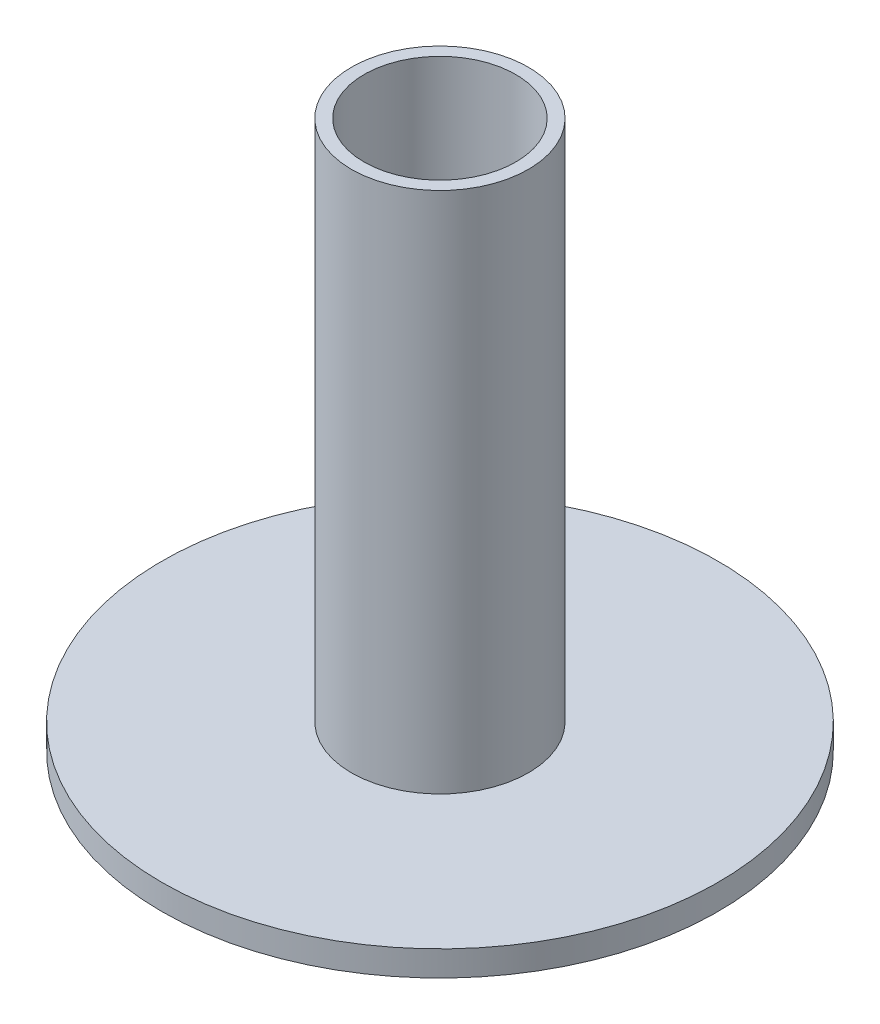
SolidWorks part; units mm, degrees
ref_plane "Alzado" through (0, 0, 0) normal (0, 0, 1) x (1, 0, 0)
ref_plane "Planta" through (0, 0, 0) normal (0, 1, 0) x (1, 0, 0)
ref_plane "Vista lateral" through (0, 0, 0) normal (1, 0, 0) x (0, 0, -1)
sketch "Croquis1" plane through (0, 0, 0) normal (0, 1, 0) x (1, 0, 0)
  circle A0 centre (0, 0) radius 33
  dimension "D1" = 66
extrude "Saliente-Extruir1" add sketch "Croquis1" along normal blind 3
sketch "Croquis2" plane through (0, 3, 0) normal (0, 1, 0) x (1, 0, 0)
  circle A0 centre (0, 0) radius 10.5
  dimension "D1" = 21
extrude "Saliente-Extruir2" add sketch "Croquis2" along normal blind 62
sketch "Croquis5" plane through (0, 0, 0) normal (0, -1, 0) x (1, 0, 0)
  circle A0 centre (0, 0) radius 8.75
  dimension "D1" = 17.5
extrude "Cortar-Extruir5" cut sketch "Croquis5" against normal blind 10
sketch "Croquis7" plane through (0, 65, 0) normal (0, 1, 0) x (1, 0, 0)
  circle A0 centre (0, 0) radius 9
  dimension "D1" = 18
extrude "Cortar-Extruir6" cut sketch "Croquis7" against normal blind 35
